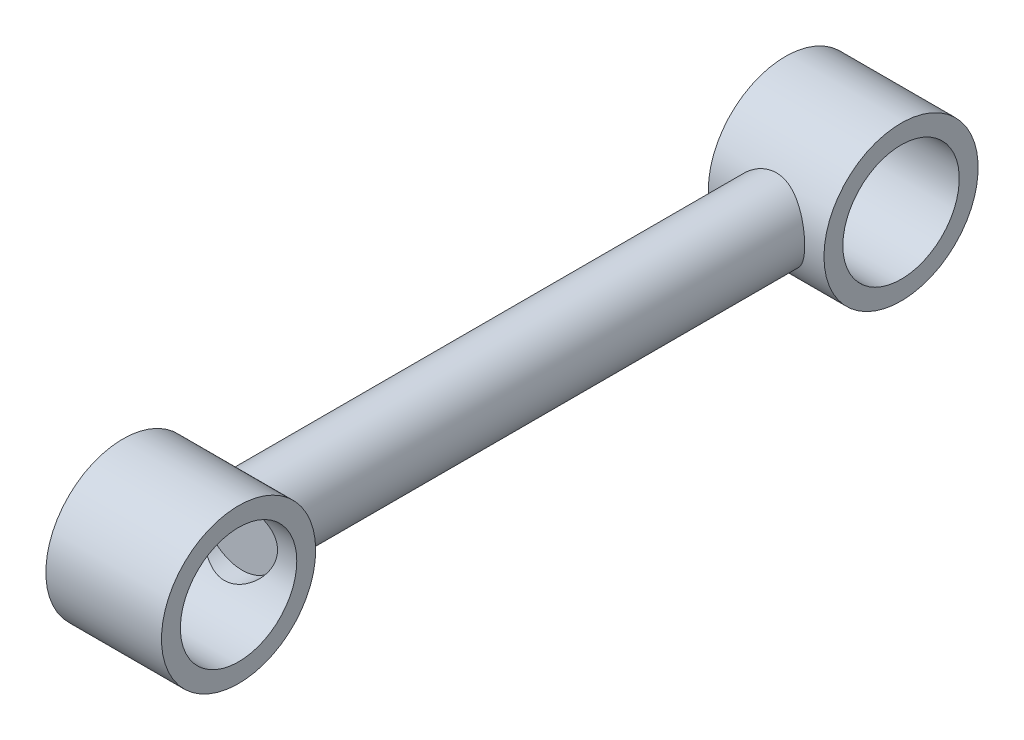
SolidWorks part; units mm, degrees
ref_plane "Front Plane" through (0, 0, 0) normal (0, 0, 1) x (1, 0, 0)
ref_plane "Top Plane" through (0, 0, 0) normal (0, 1, 0) x (1, 0, 0)
ref_plane "Right Plane" through (0, 0, 0) normal (1, 0, 0) x (0, 0, -1)
sketch "Sketch4" plane through (0, 0, 0) normal (1, 0, 0) x (0, 0, -1)
  circle A1 centre (-284.3961, 0) radius 19.177
  circle A2 centre (-284.3961, 0) radius 25.4
  dimension "D1" = 38.354
  dimension "D2" = 50.8
extrude "Boss-Extrude3" add sketch "Sketch4" along normal mid plane 38.1
ref_plane "Plane1" through (0, 0, 276.86) normal (0, 0, 1) x (1, 0, 0)
sketch "Sketch6" plane through (0, 0, 276.86) normal (0, 0, 1) x (1, 0, 0)
  circle A0 centre (0, 0) radius 12.7
  dimension "D1" = 25.4
extrude "Boss-Extrude4" add sketch "Sketch6" against normal blind 203.2
ref_plane "Plane2" through (0, 0, 175.26) normal (0, 0, -1) x (-1, 0, 0)
mirror "Mirror1" about plane through (0, 0, 175.26) normal (0, 0, -1) of "Boss-Extrude3"
sketch "Sketch7" plane through (0, 0, 276.86) normal (0, 0, 1) x (1, 0, 0)
  circle A0 centre (0, 0) radius 12.7
  dimension "D1" = 25.4
sketch "Sketch8" plane through (0, 0, 73.66) normal (0, 0, -1) x (-1, 0, 0)
  circle A0 centre (0, 0) radius 12.7
  dimension "D1" = 25.4
extrude "Cut-Extrude2" cut sketch "Sketch8" against normal blind 12.7
sketch "Sketch9" plane through (0, 0, 276.86) normal (0, 0, 1) x (1, 0, 0)
  circle A0 centre (0, 0) radius 12.7
extrude "Cut-Extrude4" cut sketch "Sketch9" against normal blind 12.7
